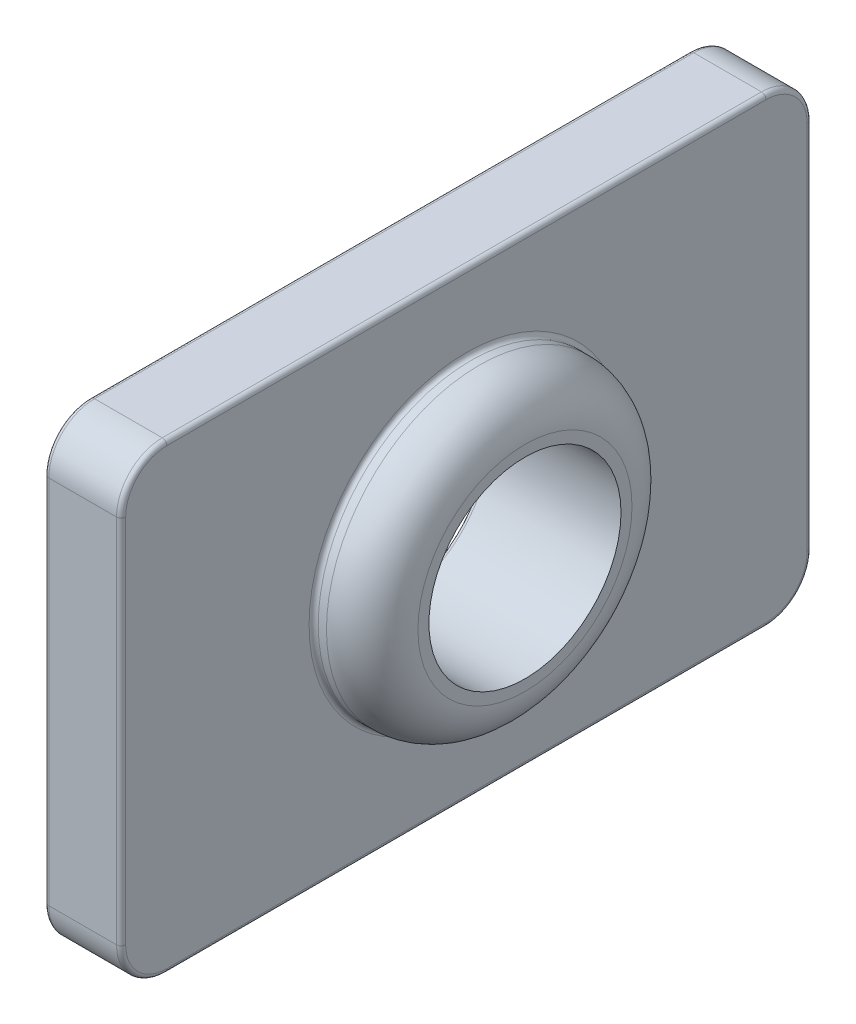
SolidWorks part; units mm, degrees
ref_plane "Front" through (0, 0, 0) normal (0, 0, 1) x (1, 0, 0)
ref_plane "Top" through (0, 0, 0) normal (0, 1, 0) x (1, 0, 0)
ref_plane "Right" through (0, 0, 0) normal (1, 0, 0) x (0, 0, -1)
sketch "Sketch1" plane through (0, 0, 0) normal (1, 0, 0) x (0, 0, -1)
  line L1 (7.55, -5.05) -> (-7.55, -5.05)
  line L2 (7.55, -5.05) -> (7.55, 5.05)
  line L3 (7.55, 5.05) -> (-7.55, 5.05)
  line L4 (-7.55, -5.05) -> (-7.55, 5.05)
  line L5 (7.55, -5.05) -> (-7.55, 5.05) construction
  line L6 (7.55, 5.05) -> (-7.55, -5.05) construction
  point P0 (0, 0)
  dimension "D1" = 15.1
  dimension "D2" = 10.1
extrude "Boss-Extrude1" add sketch "Sketch1" along normal blind 1.68
sketch "Sketch3" plane through (1.68, 0, 0) normal (1, 0, 0) x (0, 0, -1)
  circle A0 centre (0, 0) radius 3.34
  dimension "D1" = 6.68
extrude "Boss-Extrude2" add sketch "Sketch3" along normal blind 1.28
fillet "Fillet1" radius 1 1 edges at (2.96, 0, -3.34)
hole_wizard "M5x0.8 Tapped Hole1" positions "Sketch4" profile "Sketch6" tap size "M5x0.8" standard "ANSI Metric" end condition through all
sketch "Sketch4" plane through (2.96, 0, 0) normal (1, 0, 0) x (0, 0, -1)
  point P0 (0, 0)
sketch "Sketch6" plane through (2.96, 0, 0) normal (0, 1, 0) x (0, 0, -1)
  line L0 (0, 0) -> (0, 2.96)
  line L1 (0, 2.96) -> (2.1, 2.96)
  line L2 (2.1, 2.96) -> (2.1, 0)
  line L5 (2.1, 0) -> (0, 0)
  line L11 (0, -6.35) -> (0, 107.95) construction
  dimension "Thru Tap Drill Dia." = 4.2
  dimension "Thru Tap Drill Depth" = 2.96
cosmetic thread "Hole Thread1" parameters "D2"=5
fillet "Fillet2" radius 1 4 edges at (0.84, -5.05, 7.55) (0.84, -5.05, -7.55) (0.84, 5.05, -7.55) (0.84, 5.05, 7.55)
fillet "Fillet3" radius 0.1 18 edges at (0, -4.7571, -7.2571) (0, 0, -7.55) (0, 4.7571, -7.2571) (0, 5.05, 0) (0, 4.7571, 7.2571) (0, 0, 7.55) (0, -4.7571, 7.2571) (0, -5.05, 0) (0, 0, -2.1) (1.68, 4.7571, 7.2571) (1.68, 5.05, 0) (1.68, 4.7571, -7.2571) (1.68, 0, -7.55) (1.68, -4.7571, -7.2571) (1.68, -5.05, 0) (1.68, -4.7571, 7.2571) (1.68, 0, 7.55) (1.68, 0, -3.34)
